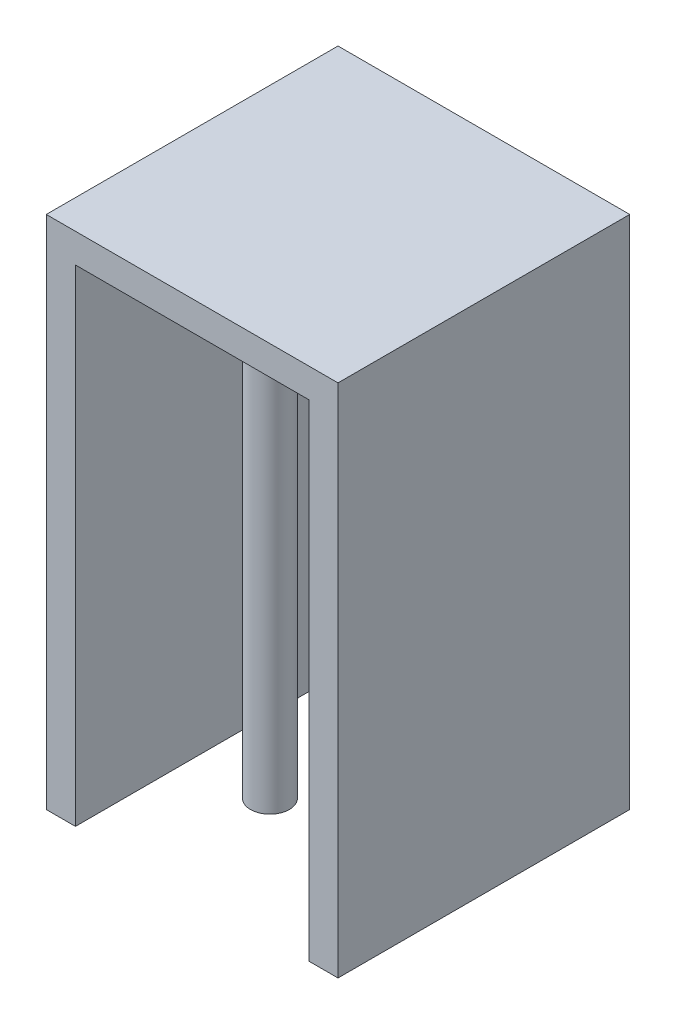
SolidWorks part; units mm, degrees
ref_plane "Alzado" through (0, 0, 0) normal (0, 0, 1) x (1, 0, 0)
ref_plane "Planta" through (0, 0, 0) normal (0, 1, 0) x (1, 0, 0)
ref_plane "Vista lateral" through (0, 0, 0) normal (1, 0, 0) x (0, 0, -1)
sketch "Croquis1" plane through (0, 0, 0) normal (0, 1, 0) x (1, 0, 0)
  line L1 (15, -15) -> (-15, -15)
  line L2 (15, -15) -> (15, 15)
  line L3 (15, 15) -> (-15, 15)
  line L4 (-15, -15) -> (-15, 15)
  line L5 (15, -15) -> (-15, 15) construction
  line L6 (15, 15) -> (-15, -15) construction
  point P0 (0, 0)
  dimension "D1" = 30
  dimension "D2" = 30
extrude "Saliente-Extruir2" add sketch "Croquis1" against normal blind 3
sketch "Croquis2" plane through (0, -3, 0) normal (0, -1, 0) x (1, 0, 0)
  line L0 (-15, 15) -> (-12, 15)
  line L1 (-15, 15) -> (15, 15) construction
  line L2 (-12, 15) -> (-12, -12)
  line L3 (15, -15) -> (-15, -15) construction
  line L4 (-12, -15) -> (-15, -15)
  line L5 (-15, -15) -> (-15, 15)
  line L6 (15, 15) -> (12, 15)
  line L7 (12, 15) -> (12, -12)
  line L8 (12, -15) -> (15, -15)
  line L9 (15, -15) -> (15, 15)
  line L10 (12, -15) -> (-12, -15)
  line L11 (-12, -12) -> (12, -12)
  dimension "D1" = 3
  dimension "D2" = 3
  dimension "D3" = 3
extrude "Saliente-Extruir3" add sketch "Croquis2" along normal blind 50
sketch "Croquis3" plane through (0, -3, 0) normal (0, -1, 0) x (1, 0, 0)
  line L0 (0, -12) -> (0, 0) construction
  line L1 (12, -12) -> (-12, -12) construction
  line L2 (0, 0) -> (7, 0) construction
  line L3 (0, 0) -> (-7, 0) construction
  circle A0 centre (-7, 0) radius 2
  circle A1 centre (7, 0) radius 2
  dimension "D3" = 4
  dimension "D4" = 4
  dimension "D1" = 7
  dimension "D2" = 7
extrude "Saliente-Extruir4" add sketch "Croquis3" along normal blind 52.5
